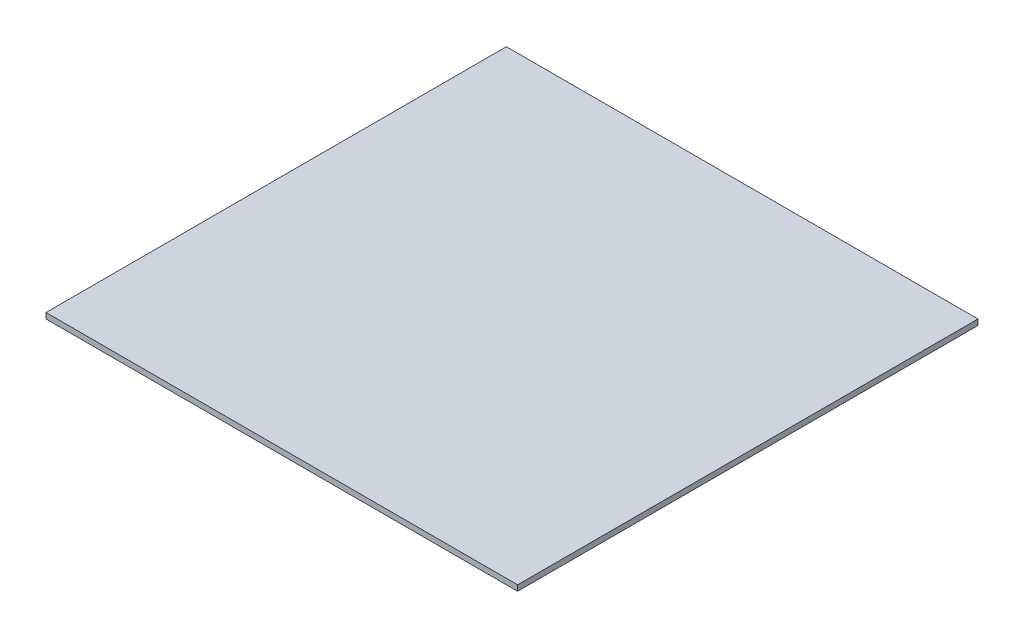
SolidWorks part; units mm, degrees
ref_plane "Front Plane" through (0, 0, 0) normal (0, 0, 1) x (1, 0, 0)
ref_plane "Top Plane" through (0, 0, 0) normal (0, 1, 0) x (1, 0, 0)
ref_plane "Right Plane" through (0, 0, 0) normal (1, 0, 0) x (0, 0, -1)
sketch "Sketch1" plane through (0, 0, 0) normal (0, 1, 0) x (1, 0, 0)
  line L1 (-533.4, -520.7) -> (533.4, -520.7)
  line L2 (-533.4, -520.7) -> (-533.4, 520.7)
  line L3 (-533.4, 520.7) -> (533.4, 520.7)
  line L4 (533.4, -520.7) -> (533.4, 520.7)
  line L5 (-533.4, -520.7) -> (533.4, 520.7) construction
  line L6 (-533.4, 520.7) -> (533.4, -520.7) construction
  point P0 (0, 0)
  dimension "D1" = 1066.8
  dimension "D2" = 1041.4
extrude "Boss-Extrude1" add sketch "Sketch1" along normal blind 12.7
